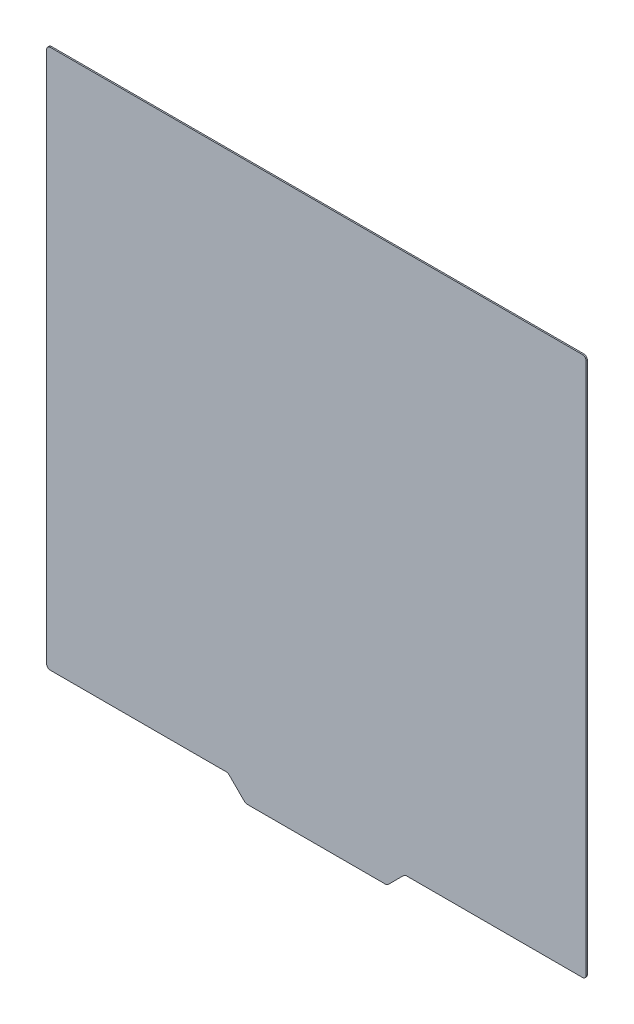
SolidWorks part; units mm, degrees
material "Cast Alloy Steel"
ref_plane "Top Plane" through (0, 0, 0) normal (0, 0, 1) x (1, 0, 0)
ref_plane "Front Plane" through (0, 0, 0) normal (0, 1, 0) x (1, 0, 0)
ref_plane "Right Plane" through (0, 0, 0) normal (1, 0, 0) x (0, 0, -1)
sketch "Sketch1" plane through (0, 0, 0) normal (0, 0, 1) x (1, 0, 0)
  line L0 (-152.5, -152.5) -> (-50, -152.5)
  line L2 (-152.5, -152.5) -> (-152.5, 152.5)
  line L3 (-152.5, 152.5) -> (152.5, 152.5)
  line L4 (152.5, -152.5) -> (152.5, 152.5)
  line L5 (-152.5, -152.5) -> (152.5, 152.5) construction
  line L6 (-152.5, 152.5) -> (152.5, -152.5) construction
  line L7 (-50, -152.5) -> (-40, -162.5)
  line L8 (-40, -162.5) -> (40, -162.5)
  line L9 (40, -162.5) -> (50, -152.5)
  line L10 (50, -152.5) -> (152.5, -152.5)
  point P0 (0, 0)
  dimension "D1" = 305
  dimension "D2" = 305
  dimension "D3" = 100
  dimension "D4" = 80
  dimension "D5" = 10
  dimension "D6" = 50
extrude "Boss-Extrude1" add sketch "Sketch1" along normal blind 0.75
fillet "Fillet1" radius 2 8 edges at (-152.5, -152.5, 0.375) (-50, -152.5, 0.375) (-40, -162.5, 0.375) (40, -162.5, 0.375) (50, -152.5, 0.375) (152.5, -152.5, 0.375) (-152.5, 152.5, 0.375) (152.5, 152.5, 0.375)
